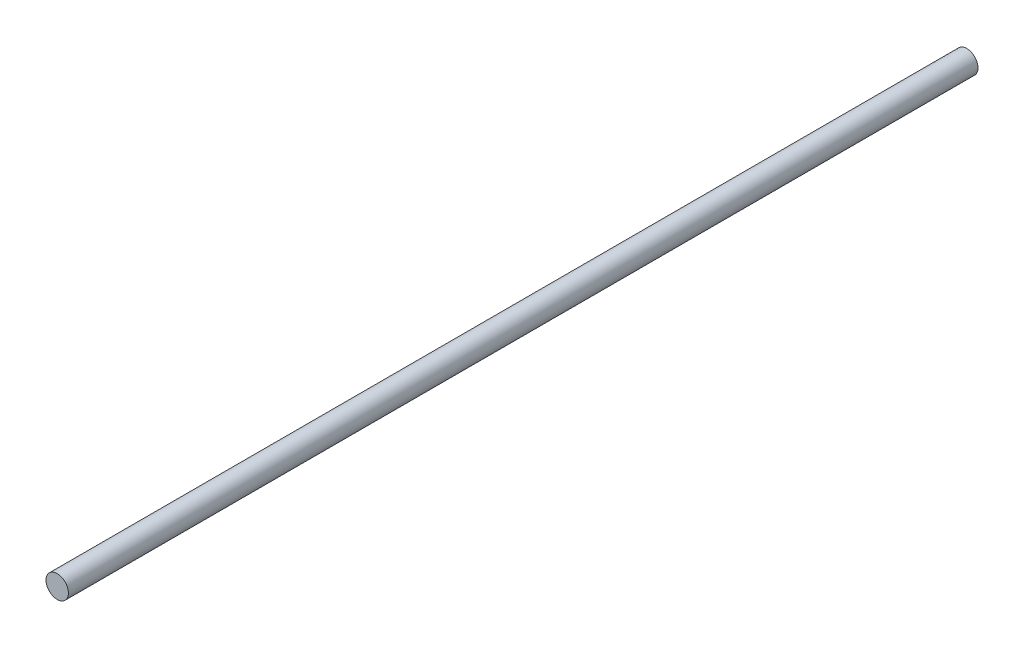
SolidWorks part; units mm, degrees
material "AISI 4130 Steel, annealed at 865C"
ref_plane "Front Plane" through (0, 0, 0) normal (0, 0, 1) x (1, 0, 0)
ref_plane "Top Plane" through (0, 0, 0) normal (0, 1, 0) x (1, 0, 0)
ref_plane "Right Plane" through (0, 0, 0) normal (1, 0, 0) x (0, 0, -1)
sketch "Sketch1" plane through (0, 0, 0) normal (0, 0, 1) x (1, 0, 0)
  circle A0 centre (0, 0) radius 12.7
  dimension "D1" = 25.4
extrude "Boss-Extrude1" add sketch "Sketch1" along normal blind 1030
